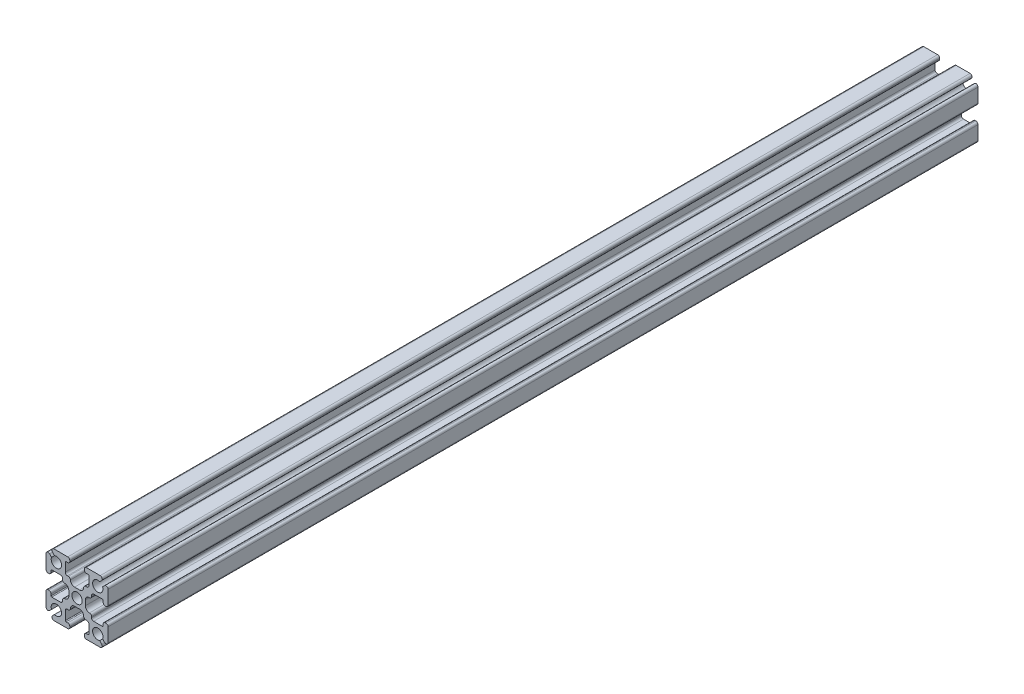
SolidWorks part; units mm, degrees
ref_plane "Front" through (0, 0, 0) normal (0, 0, 1) x (1, 0, 0)
ref_plane "Top" through (0, 0, 0) normal (0, 1, 0) x (1, 0, 0)
ref_plane "Right" through (0, 0, 0) normal (1, 0, 0) x (0, 0, -1)
sketch "Sketch1" plane through (0, 0, 0) normal (0, 0, 1) x (1, 0, 0)
  line L0 (6.6464, 5.9393) -> (6.1636, 5.4565)
  line L1 (5.4565, 6.1636) -> (5.9393, 6.6464)
  line L2 (5.5858, 7.5) -> (2.25, 7.5)
  line L3 (1.75, 7) -> (1.75, 6.8)
  line L4 (2.25, 6.3) -> (2.65, 6.3)
  line L5 (2.85, 6.1) -> (2.85, 4)
  line L6 (2.35, 3.5) -> (2.1, 3.5)
  line L7 (0.6, 2) -> (-0.6, 2)
  line L8 (-2.1, 3.5) -> (-2.35, 3.5)
  line L9 (-2.85, 4) -> (-2.85, 6.1)
  line L10 (-2.65, 6.3) -> (-2.25, 6.3)
  line L11 (-1.75, 6.8) -> (-1.75, 7)
  line L12 (-2.25, 7.5) -> (-5.5858, 7.5)
  line L13 (-5.9393, 6.6464) -> (-5.4565, 6.1636)
  line L14 (-6.1636, 5.4565) -> (-6.6464, 5.9393)
  line L15 (-7.5, 5.5858) -> (-7.5, 2.25)
  line L16 (-7, 1.75) -> (-6.8, 1.75)
  line L17 (-6.3, 2.25) -> (-6.3, 2.65)
  line L18 (-6.1, 2.85) -> (-4, 2.85)
  line L19 (-3.5, 2.35) -> (-3.5, 2.1)
  line L20 (-2, 0.6) -> (-2, -0.6)
  line L21 (-3.5, -2.1) -> (-3.5, -2.35)
  line L22 (-4, -2.85) -> (-6.1, -2.85)
  line L23 (-6.3, -2.65) -> (-6.3, -2.25)
  line L24 (-6.8, -1.75) -> (-7, -1.75)
  line L25 (-7.5, -2.25) -> (-7.5, -5.5858)
  line L26 (-6.6464, -5.9393) -> (-6.1636, -5.4565)
  line L27 (-5.4565, -6.1636) -> (-5.9393, -6.6464)
  line L28 (-5.5858, -7.5) -> (-2.25, -7.5)
  line L29 (-1.75, -7) -> (-1.75, -6.8)
  line L30 (-2.25, -6.3) -> (-2.65, -6.3)
  line L31 (-2.85, -6.1) -> (-2.85, -4)
  line L32 (-2.35, -3.5) -> (-2.1, -3.5)
  line L33 (-0.6, -2) -> (0.6, -2)
  line L34 (2.1, -3.5) -> (2.35, -3.5)
  line L35 (2.85, -4) -> (2.85, -6.1)
  line L36 (2.65, -6.3) -> (2.25, -6.3)
  line L37 (1.75, -6.8) -> (1.75, -7)
  line L38 (2.25, -7.5) -> (5.5858, -7.5)
  line L39 (5.9393, -6.6464) -> (5.4565, -6.1636)
  line L40 (6.1636, -5.4565) -> (6.6464, -5.9393)
  line L41 (7.5, -5.5858) -> (7.5, -2.25)
  line L42 (7, -1.75) -> (6.8, -1.75)
  line L43 (6.3, -2.25) -> (6.3, -2.65)
  line L44 (6.1, -2.85) -> (4, -2.85)
  line L45 (3.5, -2.35) -> (3.5, -2.1)
  line L46 (2, -0.6) -> (2, 0.6)
  line L47 (3.5, 2.1) -> (3.5, 2.35)
  line L48 (4, 2.85) -> (6.1, 2.85)
  line L49 (6.3, 2.65) -> (6.3, 2.25)
  line L50 (6.8, 1.75) -> (7, 1.75)
  line L51 (7.5, 2.25) -> (7.5, 5.5858)
  circle A0 centre (0, 0) radius 1.25
  arc A1 (6.1636, 5.4565) -> (5.4565, 6.1636) centre (5, 5) cw
  arc A2 (5.9393, 6.6464) -> (5.5858, 7.5) centre (5.5858, 7) ccw
  arc A3 (2.25, 7.5) -> (1.75, 7) centre (2.25, 7) ccw
  arc A4 (1.75, 6.8) -> (2.25, 6.3) centre (2.25, 6.8) ccw
  arc A5 (2.65, 6.3) -> (2.85, 6.1) centre (2.65, 6.1) cw
  arc A6 (2.85, 4) -> (2.35, 3.5) centre (2.35, 4) cw
  arc A7 (2.1, 3.5) -> (1.6, 3) centre (2.1, 3) ccw
  arc A8 (1.6, 3) -> (0.6, 2) centre (0.6, 3) cw
  arc A9 (-0.6, 2) -> (-1.6, 3) centre (-0.6, 3) cw
  arc A10 (-1.6, 3) -> (-2.1, 3.5) centre (-2.1, 3) ccw
  arc A11 (-2.35, 3.5) -> (-2.85, 4) centre (-2.35, 4) cw
  arc A12 (-2.85, 6.1) -> (-2.65, 6.3) centre (-2.65, 6.1) cw
  arc A13 (-2.25, 6.3) -> (-1.75, 6.8) centre (-2.25, 6.8) ccw
  arc A14 (-1.75, 7) -> (-2.25, 7.5) centre (-2.25, 7) ccw
  arc A15 (-5.5858, 7.5) -> (-5.9393, 6.6464) centre (-5.5858, 7) ccw
  arc A16 (-5.4565, 6.1636) -> (-6.1636, 5.4565) centre (-5, 5) cw
  arc A17 (-6.6464, 5.9393) -> (-7.5, 5.5858) centre (-7, 5.5858) ccw
  arc A18 (-7.5, 2.25) -> (-7, 1.75) centre (-7, 2.25) ccw
  arc A19 (-6.8, 1.75) -> (-6.3, 2.25) centre (-6.8, 2.25) ccw
  arc A20 (-6.3, 2.65) -> (-6.1, 2.85) centre (-6.1, 2.65) cw
  arc A21 (-4, 2.85) -> (-3.5, 2.35) centre (-4, 2.35) cw
  arc A22 (-3.5, 2.1) -> (-3, 1.6) centre (-3, 2.1) ccw
  arc A23 (-3, 1.6) -> (-2, 0.6) centre (-3, 0.6) cw
  arc A24 (-2, -0.6) -> (-3, -1.6) centre (-3, -0.6) cw
  arc A25 (-3, -1.6) -> (-3.5, -2.1) centre (-3, -2.1) ccw
  arc A26 (-3.5, -2.35) -> (-4, -2.85) centre (-4, -2.35) cw
  arc A27 (-6.1, -2.85) -> (-6.3, -2.65) centre (-6.1, -2.65) cw
  arc A28 (-6.3, -2.25) -> (-6.8, -1.75) centre (-6.8, -2.25) ccw
  arc A29 (-7, -1.75) -> (-7.5, -2.25) centre (-7, -2.25) ccw
  arc A30 (-7.5, -5.5858) -> (-6.6464, -5.9393) centre (-7, -5.5858) ccw
  arc A31 (-6.1636, -5.4565) -> (-5.4565, -6.1636) centre (-5, -5) cw
  arc A32 (-5.9393, -6.6464) -> (-5.5858, -7.5) centre (-5.5858, -7) ccw
  arc A33 (-2.25, -7.5) -> (-1.75, -7) centre (-2.25, -7) ccw
  arc A34 (-1.75, -6.8) -> (-2.25, -6.3) centre (-2.25, -6.8) ccw
  arc A35 (-2.65, -6.3) -> (-2.85, -6.1) centre (-2.65, -6.1) cw
  arc A36 (-2.85, -4) -> (-2.35, -3.5) centre (-2.35, -4) cw
  arc A37 (-2.1, -3.5) -> (-1.6, -3) centre (-2.1, -3) ccw
  arc A38 (-1.6, -3) -> (-0.6, -2) centre (-0.6, -3) cw
  arc A39 (0.6, -2) -> (1.6, -3) centre (0.6, -3) cw
  arc A40 (1.6, -3) -> (2.1, -3.5) centre (2.1, -3) ccw
  arc A41 (2.35, -3.5) -> (2.85, -4) centre (2.35, -4) cw
  arc A42 (2.85, -6.1) -> (2.65, -6.3) centre (2.65, -6.1) cw
  arc A43 (2.25, -6.3) -> (1.75, -6.8) centre (2.25, -6.8) ccw
  arc A44 (1.75, -7) -> (2.25, -7.5) centre (2.25, -7) ccw
  arc A45 (5.5858, -7.5) -> (5.9393, -6.6464) centre (5.5858, -7) ccw
  arc A46 (5.4565, -6.1636) -> (6.1636, -5.4565) centre (5, -5) cw
  arc A47 (6.6464, -5.9393) -> (7.5, -5.5858) centre (7, -5.5858) ccw
  arc A48 (7.5, -2.25) -> (7, -1.75) centre (7, -2.25) ccw
  arc A49 (6.8, -1.75) -> (6.3, -2.25) centre (6.8, -2.25) ccw
  arc A50 (6.3, -2.65) -> (6.1, -2.85) centre (6.1, -2.65) cw
  arc A51 (4, -2.85) -> (3.5, -2.35) centre (4, -2.35) cw
  arc A52 (3.5, -2.1) -> (3, -1.6) centre (3, -2.1) ccw
  arc A53 (3, -1.6) -> (2, -0.6) centre (3, -0.6) cw
  arc A54 (2, 0.6) -> (3, 1.6) centre (3, 0.6) cw
  arc A55 (3, 1.6) -> (3.5, 2.1) centre (3, 2.1) ccw
  arc A56 (3.5, 2.35) -> (4, 2.85) centre (4, 2.35) cw
  arc A57 (6.1, 2.85) -> (6.3, 2.65) centre (6.1, 2.65) cw
  arc A58 (6.3, 2.25) -> (6.8, 1.75) centre (6.8, 2.25) ccw
  arc A59 (7, 1.75) -> (7.5, 2.25) centre (7, 2.25) ccw
  arc A60 (7.5, 5.5858) -> (6.6464, 5.9393) centre (7, 5.5858) ccw
extrude "Boss-Extrude1" add sketch "Sketch1" along normal blind 210
